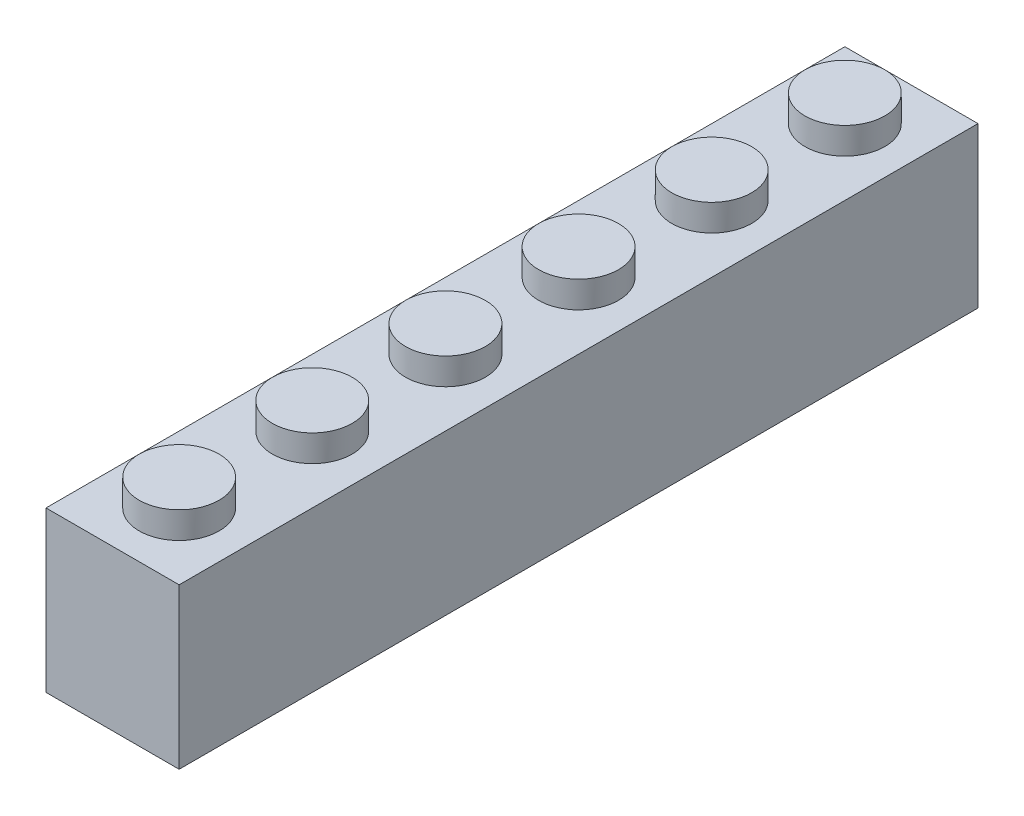
SolidWorks part; units mm, degrees
ref_plane "Front Plane" through (0, 0, 0) normal (0, 0, 1) x (1, 0, 0)
ref_plane "Top Plane" through (0, 0, 0) normal (0, 1, 0) x (1, 0, 0)
ref_plane "Right Plane" through (0, 0, 0) normal (1, 0, 0) x (0, 0, -1)
sketch "Sketch1" plane through (0, 0, 0) normal (0, 1, 0) x (1, 0, 0)
  line L1 (0, 0) -> (8, 0)
  line L2 (0, 0) -> (0, 48)
  line L3 (0, 48) -> (8, 48)
  line L4 (8, 0) -> (8, 48)
  dimension "D1" = 8
  dimension "D2" = 48
extrude "Boss-Extrude1" add sketch "Sketch1" along normal blind 9.6
sketch "Sketch2" plane through (0, 9.6, 0) normal (0, 1, 0) x (1, 0, 0)
  line L0 (4, 0) -> (4, 48) construction
  line L1 (0, 0) -> (8, 0) construction
  line L2 (8, 48) -> (0, 48) construction
  line L3 (8, 0) -> (8, 4) construction
  line L4 (8, 0) -> (8, 48) construction
  line L5 (8, 4) -> (4, 4) construction
  circle A0 centre (4, 4) radius 2.4
  dimension "D3" = 4.8
  dimension "D1" = 4
  dimension "D2" = 4
extrude "Boss-Extrude2" add sketch "Sketch2" along normal blind 1.6
pattern_linear "LPattern1" count 2 spacing 8 along (1, 0, 0) count 6 spacing 8 along (0, 0, -1) of "Boss-Extrude2"
shell "Shell1" thickness 1.6
